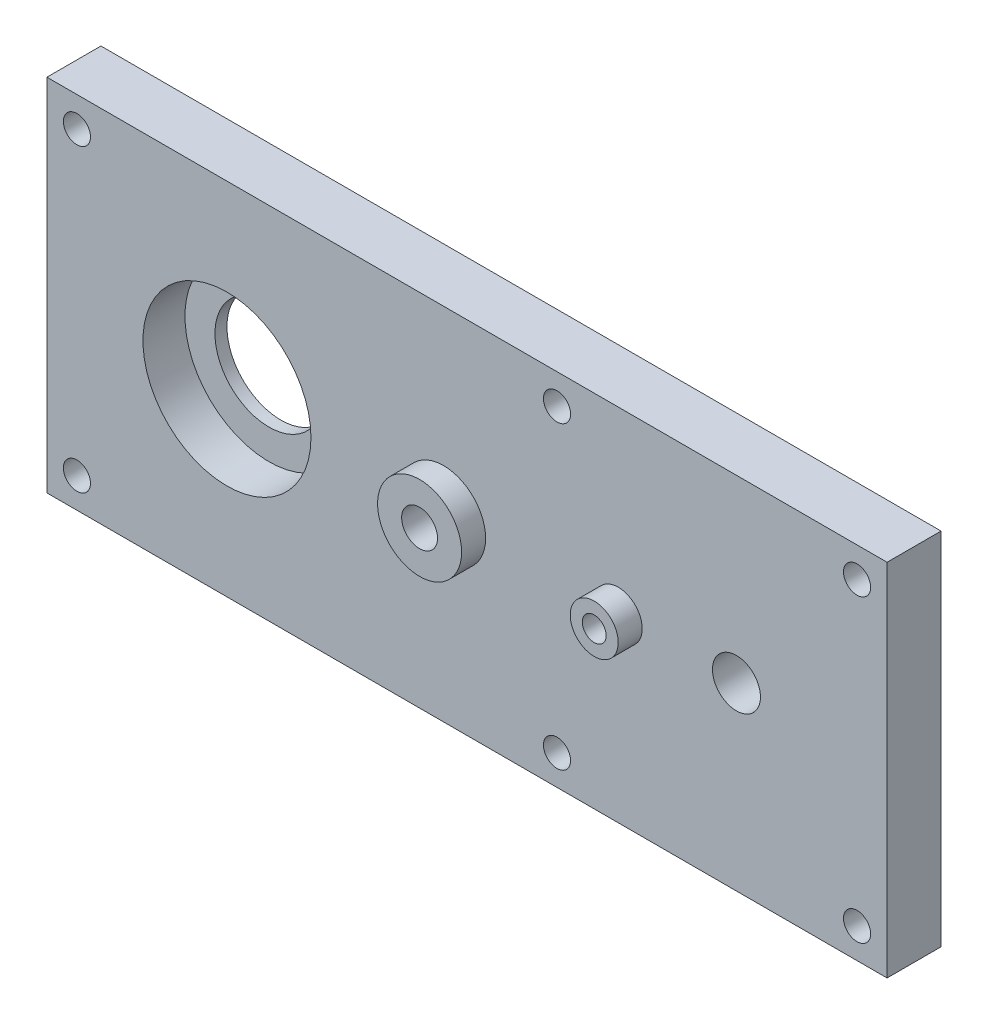
SolidWorks part; units mm, degrees
material "6061-T6 (SS)"
ref_plane "Front Plane" through (0, 0, 0) normal (0, 0, 1) x (1, 0, 0)
ref_plane "Top Plane" through (0, 0, 0) normal (0, 1, 0) x (1, 0, 0)
ref_plane "Right Plane" through (0, 0, 0) normal (1, 0, 0) x (0, 0, -1)
sketch "Sketch1" plane through (0, 0, 0) normal (0, 0, 1) x (1, 0, 0)
  line L0 (0, 0) -> (18.05, 0) construction
  line L1 (18.05, 0) -> (32.6, 0) construction
  line L2 (32.6, 0) -> (42.45, 0) construction
  line L3 (0, 0) -> (-15, 0) construction
  line L4 (-15, 15) -> (55, 15)
  line L5 (-15, 15) -> (-15, -15)
  line L6 (-15, -15) -> (55, -15)
  line L7 (55, 15) -> (55, -15)
  circle A0 centre (0, 0) radius 4.5
  circle A1 centre (18.05, 0) radius 1.495
  circle A2 centre (32.6, 0) radius 0.995
  circle A3 centre (42.45, 0) radius 2
  circle A4 centre (42.45, 0) radius 12 construction
  circle A5 centre (0, 0) radius 13.35 construction
  circle A6 centre (18.05, 0) radius 11.9 construction
  dimension "D1" = 9
  dimension "D2" = 2.99
  dimension "D4" = 1.99
  dimension "D6" = 4
  dimension "D10" = 24
  dimension "D12" = 26.7
  dimension "D13" = 23.8
  dimension "D3" = 18.05
  dimension "D5" = 14.55
  dimension "D7" = 9.85
  dimension "D8" = 30
  dimension "D9" = 15
  dimension "D11" = 70
extrude "Boss-Extrude1" add sketch "Sketch1" along normal blind 4.5
hole_wizard "#2 Clearance Hole1" positions "Sketch5" profile "Sketch4" hole size "#2" standard "ANSI Inch" end condition through all
sketch "Sketch5" plane through (0, 0, 4.5) normal (0, 0, 1) x (1, 0, 0)
  line L0 (-12.5, -12.5) -> (-12.5, 12.5) construction
  line L1 (-12.5, 12.5) -> (27.5, 12.5) construction
  line L5 (27.5, -12.5) -> (27.5, 12.5) construction
  line L7 (-12.5, -12.5) -> (27.5, -12.5) construction
  line L9 (-15, 15) -> (-15, -15) construction
  line L10 (55, 15) -> (-15, 15) construction
  line L11 (-15, -15) -> (55, -15) construction
  line L12 (27.5, -12.5) -> (52.5, -12.5) construction
  line L13 (52.5, -12.5) -> (52.5, 12.5) construction
  line L14 (52.5, 12.5) -> (27.5, 12.5) construction
  line L16 (55, -15) -> (55, 15) construction
  point P0 (-12.5, 12.5)
  point P2 (-12.5, -12.5)
  point P8 (27.5, 12.5)
  point P10 (27.5, -12.5)
  point P37 (52.5, 12.5)
  point P39 (52.5, -12.5)
  dimension "D1" = 2.5
  dimension "D2" = 2.5
  dimension "D3" = 2.5
  dimension "D4" = 2.5
  dimension "D5" = 40
sketch "Sketch4" plane through (-12.5, 12.5, 4.5) normal (1, 0, 0) x (0, -1, 0)
  line L0 (0, 0) -> (0, 4.5)
  line L1 (0, 4.5) -> (1.1303, 4.5)
  line L2 (1.1303, 4.5) -> (1.1303, 0)
  line L5 (1.1303, 0) -> (0, 0)
  line L11 (0, -6.35) -> (0, 107.95) construction
  dimension "Thru Hole Dia." = 2.2606
  dimension "Thru Hole Depth" = 4.5
sketch "Sketch6" plane through (0, 0, 4.5) normal (0, 0, 1) x (1, 0, 0)
  circle A0 centre (0, 0) radius 7
  dimension "D1" = 14
extrude "Cut-Extrude1" cut sketch "Sketch6" against normal blind 3.5
sketch "Sketch7" plane through (0, 0, 4.5) normal (0, 0, 1) x (1, 0, 0)
  circle A0 centre (18.05, 0) radius 3.5
  circle A1 centre (18.05, 0) radius 1.495 construction
  circle A2 centre (18.05, 0) radius 1.495
  dimension "D1" = 7
extrude "Boss-Extrude2" add sketch "Sketch7" along normal blind 2
sketch "Sketch8" plane through (0, 0, 4.5) normal (0, 0, 1) x (1, 0, 0)
  circle A0 centre (32.6, 0) radius 2
  circle A1 centre (32.6, 0) radius 0.995 construction
  circle A2 centre (32.6, 0) radius 0.995
  dimension "D1" = 4
extrude "Boss-Extrude3" add sketch "Sketch8" along normal blind 2
